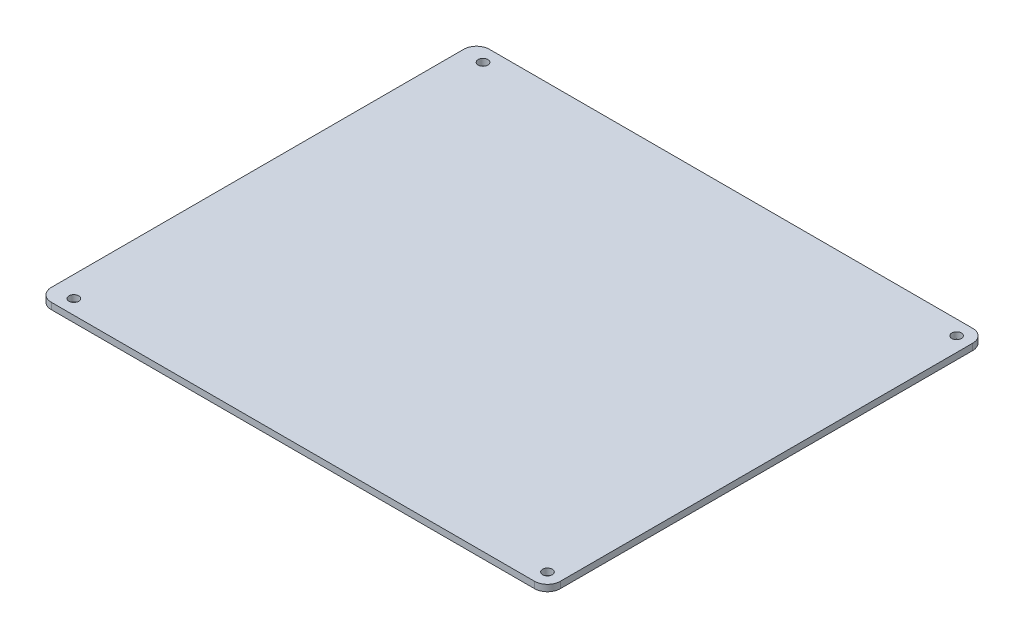
SolidWorks part; units mm, degrees
ref_plane "Front Plane" through (0, 0, 0) normal (0, 0, 1) x (1, 0, 0)
ref_plane "Top Plane" through (0, 0, 0) normal (0, 1, 0) x (1, 0, 0)
ref_plane "Right Plane" through (0, 0, 0) normal (1, 0, 0) x (0, 0, -1)
sketch "Sketch8" plane through (0, 0, 0) normal (0, 1, 0) x (1, 0, 0)
  line L0 (79, 0) -> (65.8191, 0) construction
  line L1 (-79, 68) -> (79, 68)
  line L2 (-79, 68) -> (-79, -68)
  line L3 (-79, -68) -> (79, -68)
  line L4 (79, 68) -> (79, -68)
  circle A0 centre (74.5, 63.5) radius 1.5
  circle A1 centre (-72.5, 63.5) radius 1.5
  circle A2 centre (-72.5, -63.5) radius 1.5
  circle A3 centre (74.5, -63.5) radius 1.5
  point P0 (0, 0)
  dimension "D3" = 3
  dimension "D4" = 4.5
  dimension "D5" = 4.5
  dimension "D6" = 4.5
  dimension "D7" = 6.5
  dimension "D1" = 136
  dimension "D2" = 158
extrude "Boss-Extrude4" add sketch "Sketch8" along normal blind 2
fillet "Fillet2" radius 4 4 edges at (-79, 1, 68) (-79, 1, -68) (79, 1, -68) (79, 1, 68)
sketch "Sketch10" plane through (0, 0, 0) normal (0, -1, 0) x (1, 0, 0)
  line L0 (-79, 0) -> (79, 0) construction
  line L1 (-79, -64) -> (-79, 64) construction
  line L2 (79, 64) -> (79, -64) construction
  line L3 (-65.5, 51) -> (-65.5, -51)
  line L4 (-63.5, 55) -> (63.5, 55)
  line L5 (-67.5, 51) -> (-67.5, -51)
  line L6 (-63.5, -55) -> (63.5, -55)
  line L7 (67.5, 51) -> (67.5, -51)
  line L8 (-67.5, 55) -> (67.5, -55) construction
  line L9 (-67.5, -55) -> (67.5, 55) construction
  line L10 (-63.5, -53) -> (63.5, -53)
  line L11 (65.5, 51) -> (65.5, -51)
  line L12 (-63.5, 53) -> (63.5, 53)
  arc A0 (63.5, 55) -> (67.5, 51) centre (63.5, 51) cw
  arc A1 (63.5, -55) -> (67.5, -51) centre (63.5, -51) ccw
  arc A2 (-67.5, -51) -> (-63.5, -55) centre (-63.5, -51) ccw
  arc A3 (-63.5, 55) -> (-67.5, 51) centre (-63.5, 51) ccw
  arc A4 (-65.5, -51) -> (-63.5, -53) centre (-63.5, -51) ccw
  arc A5 (63.5, -53) -> (65.5, -51) centre (63.5, -51) ccw
  arc A6 (63.5, 53) -> (65.5, 51) centre (63.5, 51) cw
  arc A7 (-63.5, 53) -> (-65.5, 51) centre (-63.5, 51) ccw
  point P6 (0, 0)
  dimension "D3" = 4
  dimension "D1" = 110
  dimension "D2" = 135
  dimension "D4" = 2
extrude "Cut-Extrude1" cut sketch "Sketch10" against normal blind 0.5
sketch "Sketch11" plane through (0, 0, 0) normal (0, -1, 0) x (1, 0, 0)
  line L0 (-65.5, 0) -> (65.5, 0) construction
  line L1 (-65.5, 51) -> (-65.5, -51) construction
  line L2 (65.5, -51) -> (65.5, 51) construction
  line L3 (-63.5, -53) -> (63.5, -53) construction
  line L4 (-55.5, 48) -> (-8.6138, 48)
  line L5 (-59.5, 44) -> (-59.5, -44)
  line L6 (-55.5, -48) -> (-8.6138, -48)
  line L7 (-4.6138, 44) -> (-4.6138, -44)
  line L8 (63.5, 53) -> (-63.5, 53) construction
  line L9 (-57.6, 44) -> (-57.6, -44)
  line L10 (-55.5, -46.1) -> (-8.6138, -46.1)
  line L11 (-6.5138, 44) -> (-6.5138, -44)
  line L12 (-55.5, 46.1) -> (-8.6138, 46.1)
  arc A0 (-59.5, -44) -> (-55.5, -48) centre (-55.5, -44) ccw
  arc A1 (-8.6138, -48) -> (-4.6138, -44) centre (-8.6138, -44) ccw
  arc A2 (-8.6138, 48) -> (-4.6138, 44) centre (-8.6138, 44) cw
  arc A3 (-55.5, 48) -> (-59.5, 44) centre (-55.5, 44) ccw
  arc A4 (-57.6, -44) -> (-55.5, -46.1) centre (-55.5, -44) ccw
  arc A5 (-8.6138, -46.1) -> (-6.5138, -44) centre (-8.6138, -44) ccw
  arc A6 (-8.6138, 46.1) -> (-6.5138, 44) centre (-8.6138, 44) cw
  arc A7 (-55.5, 46.1) -> (-57.6, 44) centre (-55.5, 44) ccw
  point P6 (-35.3166, 0)
  dimension "D1" = 6
  dimension "D2" = 5
  dimension "D3" = 5
  dimension "D4" = 1.9
extrude "Cut-Extrude2" cut sketch "Sketch11" against normal blind 0.5
sketch "Sketch13" plane through (0, 0, 0) normal (0, -1, 0) x (1, 0, 0)
  line L0 (-34.5138, 46) -> (-34.5138, -46) construction
  line L8 (-6.5138, -44) -> (-6.5138, 44) construction
  text T0 "<b>DIKI DARMAWAN</b>\r\n<b>166221064</b>" font "Century Gothic" height in points 24
  dimension "D1" = 28
extrude "Cut-Extrude3" cut sketch "Sketch13" against normal blind 0.5
sketch "Sketch14" plane through (78.7715, 0, -11.0784) normal (0, -1, 0) x (0, 0, 1)
  line L0 (14.3942, 39.3839) -> (14.3942, 38.6607)
  line L1 (14.3942, 38.6607) -> (27.9652, 38.6607)
  line L2 (27.9652, 38.6607) -> (27.9652, 39.1819)
  line L3 (14.3942, 39.3839) -> (24.5365, 39.3839)
  line L4 (24.5365, 39.3839) -> (22.4336, 41.6588)
  line L5 (28.3243, 44.7624) -> (31.9276, 50.2377)
  line L6 (31.9276, 50.2377) -> (32.9334, 50.1306)
  line L7 (33.593, 50.9135) -> (33.0775, 52.0553)
  line L8 (33.0775, 52.0553) -> (37.232, 58.3682)
  line L9 (39.4319, 57.602) -> (43.2952, 51.9087)
  line L10 (43.2952, 51.9087) -> (43.2193, 50.9273)
  line L11 (43.7452, 50.1523) -> (44.5304, 50.002)
  line L12 (44.5304, 50.002) -> (47.4367, 45.7189)
  line L13 (46.1277, 44.114) -> (46.1277, 39.7648)
  line L14 (46.1277, 39.7648) -> (45.8984, 39.7648)
  line L15 (45.8984, 39.7648) -> (45.5136, 39.4091)
  line L16 (45.5136, 39.4091) -> (45.5136, 36.4852)
  line L17 (45.5136, 36.4852) -> (45.8984, 36.0689)
  line L18 (45.8984, 36.0689) -> (46.1277, 36.0689)
  line L19 (46.1277, 36.0689) -> (46.1277, 32.808)
  line L20 (46.1277, 32.808) -> (41.5903, 32.808)
  line L21 (41.5903, 32.808) -> (41.5903, 31.7995)
  line L22 (41.5903, 31.7995) -> (45.8082, 31.7995)
  line L23 (45.8082, 31.7995) -> (45.8082, 30.5822)
  line L24 (45.8082, 30.5822) -> (42.5, 30.5822)
  line L25 (41.7043, 29.6881) -> (41.7043, 24.6699)
  line L26 (41.7043, 24.6699) -> (39.9694, 24.6699)
  line L27 (39.9694, 24.6699) -> (39.9694, 17.6419)
  line L28 (39.9694, 17.6419) -> (58.0715, 17.6419)
  line L29 (58.0715, 17.6419) -> (58.0715, 24.6699)
  line L30 (58.0715, 24.6699) -> (56.627, 24.6699)
  line L31 (56.627, 24.6699) -> (56.627, 29.7373)
  line L32 (55.8459, 30.5822) -> (53.1384, 30.5822)
  line L33 (53.1384, 30.5822) -> (53.1384, 31.7995)
  line L34 (53.1384, 31.7995) -> (56.6276, 31.7995)
  line L35 (56.6276, 31.7995) -> (56.6276, 32.808)
  line L36 (56.6276, 32.808) -> (52.9298, 32.808)
  line L37 (52.9298, 32.808) -> (52.9298, 44.5866)
  line L38 (52.9298, 44.5866) -> (52.7465, 48.0931)
  line L39 (52.7465, 48.0931) -> (44.6522, 60.2848)
  line L40 (44.6522, 60.2848) -> (43.0464, 61.2259)
  line L41 (38.0429, 65.0973) -> (33.3028, 63.2191)
  line L42 (33.3028, 63.2191) -> (23.6089, 48.4889)
  line L43 (23.6089, 48.4889) -> (23.6089, 45.3452)
  line L44 (23.6089, 45.3452) -> (22.5152, 44.114)
  line L45 (25.4242, 46.0787) -> (34.6473, 59.8967)
  line L46 (35.926, 59.0433) -> (26.7841, 45.1709)
  line L47 (40.8051, 58.4574) -> (48.9052, 46.3692)
  line L48 (48.9052, 46.3692) -> (50.0331, 46.3692)
  line L49 (50.0331, 46.3692) -> (41.5903, 58.9689)
  line L50 (43.7452, 59.6351) -> (51.836, 47.4485) construction
  line L59 (45.8082, 30.5822) -> (53.1384, 30.5822)
  line L60 (41.7043, 24.6699) -> (56.627, 24.6699)
  line L61 (43.3305, 22.081) -> (45.974, 22.081)
  line L62 (43.3305, 22.081) -> (43.3305, 18.6903)
  line L63 (43.3305, 18.6903) -> (45.974, 18.6903)
  line L64 (45.974, 22.081) -> (45.974, 18.6903)
  line L65 (43.3305, 22.081) -> (45.974, 18.6903) construction
  line L66 (43.3305, 18.6903) -> (45.974, 22.081) construction
  line L67 (46.1277, 41.9394) -> (52.9298, 41.9394) construction
  line L68 (51.6208, 43.614) -> (51.1208, 44.114)
  line L69 (51.1208, 44.114) -> (47.9367, 44.114)
  line L70 (51.6208, 43.614) -> (51.6208, 40.2648)
  line L71 (51.1208, 39.7648) -> (47.9367, 39.7648)
  line L72 (47.4367, 43.614) -> (47.4367, 40.2648)
  line L73 (51.6208, 44.114) -> (47.4367, 39.7648) construction
  line L74 (51.6208, 39.7648) -> (47.4367, 44.114) construction
  line L75 (47.9367, 44.114) -> (47.4367, 43.614)
  line L76 (47.9367, 39.7648) -> (47.4367, 40.2648)
  line L77 (51.6208, 40.2648) -> (51.1208, 39.7648)
  line L78 (52.9298, 32.808) -> (46.1277, 32.808)
  line L79 (53.1384, 31.7995) -> (45.8082, 31.7995)
  line L80 (51.6208, 32.808) -> (51.6208, 36.3852)
  line L81 (51.5208, 36.4852) -> (50.6923, 36.4852)
  line L82 (50.5923, 36.3852) -> (50.5923, 32.808)
  line L83 (49.5287, 39.7648) -> (49.5287, 38.4099) construction
  line L84 (48.4652, 36.3852) -> (48.4652, 32.808)
  line L85 (47.5367, 36.4852) -> (48.3652, 36.4852)
  line L86 (47.4367, 32.808) -> (47.4367, 36.3852)
  line L87 (48.3652, 36.4852) -> (48.4652, 36.3852)
  line L88 (47.4367, 36.3852) -> (47.5367, 36.4852)
  line L89 (50.6923, 36.4852) -> (50.5923, 36.3852)
  line L90 (51.6208, 36.3852) -> (51.5208, 36.4852)
  arc A0 (27.9652, 39.1819) -> (28.1911, 43.944) centre (26.2751, 41.6485) ccw
  arc A1 (28.3243, 44.7624) -> (28.1911, 43.944) centre (28.6669, 44.2866) ccw
  arc A2 (32.9334, 50.1306) -> (33.593, 50.9135) centre (32.8712, 50.8523) ccw
  arc A3 (37.232, 58.3682) -> (39.4319, 57.602) centre (39.1848, 60.4336) ccw
  arc A4 (43.2193, 50.9273) -> (43.7452, 50.1523) centre (43.8697, 50.8028) ccw
  arc A5 (47.4367, 45.7189) -> (46.1277, 44.114) centre (48.2487, 43.7203) ccw
  arc A6 (42.5, 30.5822) -> (41.7043, 29.6881) centre (42.5492, 29.7373) ccw
  arc A7 (56.627, 29.7373) -> (55.8459, 30.5822) centre (55.814, 29.7692) ccw
  arc A8 (43.0464, 61.2259) -> (41.4746, 62.8115) centre (41.718, 61.4809) ccw
  arc A9 (41.4746, 62.8115) -> (38.0429, 65.0973) centre (38.6158, 62.2385) ccw
  arc A10 (22.5152, 44.114) -> (22.4336, 41.6588) centre (22.08, 42.8995) ccw
  arc A11 (25.4242, 46.0787) -> (26.7841, 45.1709) centre (26.2109, 45.7847) ccw
  arc A12 (34.6473, 59.8967) -> (35.926, 59.0433) centre (35.1931, 59.3298) cw
  arc A13 (40.8051, 58.4574) -> (41.5903, 58.9689) centre (41.1348, 58.8098) cw
  circle A14 centre (25.9948, 41.0458) radius 0.2321
  circle A15 centre (25.9948, 41.0458) radius 0.7503
  circle A16 centre (38.1639, 59.6351) radius 0.3438
  circle A17 centre (38.1639, 59.6351) radius 0.7446
  circle A18 centre (43.7452, 59.6351) radius 0.3297
  circle A19 centre (47.7906, 53.5418) radius 0.2839
  circle A20 centre (51.836, 47.4485) radius 0.2654
  circle A21 centre (47.974, 20.1444) radius 0.6328
  point P92 (44.6522, 20.3856)
  point P95 (49.5287, 41.9394)
  point P113 (51.6208, 36.4852)
  point P115 (50.5923, 36.4852)
  point P118 (48.4652, 36.4852)
  point P120 (47.4367, 36.4852)
  dimension "D1" = 2
extrude "Cut-Extrude5" cut sketch "Sketch14" against normal blind 0.5 contours L60 L26 L27 L28 L29 L30 A21 L61 L64 L63 L62 | L31 A7 L32 L59 L24 A6 L25 L60 | L79 L34 L35 L36 L78 L20 L21 L22 | L44 A10 L4 L3 L0 L1 L2 A0 A1 L5 L6 A2 L7 L8 A3 L9 L10 A4 L11 L12 A5 L13 L14 L15 L16 L17 L18 L19 L78 L86 L88 L85 L87 L84 L82 L89 L81 L90 L80 L37 L38 L39 L40 A8 A9 L41 L42 L43
sketch "Sketch15" plane through (-2.5633, 0, -56.8673) normal (0, -1, 0) x (0, 0, 1)
  line L0 (10.2975, -55.1047) -> (10.2975, -59.7552)
  line L1 (13.2978, -59.7552) -> (13.2978, -55.1047)
  line L2 (13.2978, -55.1047) -> (16.2026, -55.1047)
  line L3 (16.2026, -55.1047) -> (16.2026, -62.6486)
  line L4 (19.2148, -62.6486) -> (19.2148, -55.1047)
  line L5 (19.2148, -55.1047) -> (20.6726, -55.1047)
  line L6 (20.6726, -55.1047) -> (20.6726, -56.8684)
  line L7 (23.6407, -56.8684) -> (23.6407, -53.4424)
  line L8 (26.5927, -53.4424) -> (26.5927, -56.8684)
  line L9 (29.5754, -56.8684) -> (29.5754, -53.4424)
  line L10 (32.5183, -53.4424) -> (32.5183, -59.7552)
  line L11 (35.4991, -59.7552) -> (35.4991, -53.4424)
  line L12 (38.4074, -53.4424) -> (38.4074, -56.8684)
  line L13 (41.4124, -53.4424) -> (41.4124, -56.8684)
  line L14 (44.3284, -53.4424) -> (44.3284, -59.7552)
  line L15 (47.3334, -53.4424) -> (47.3334, -59.7552)
  line L16 (50.2716, -59.7552) -> (50.2716, -53.4424)
  line L17 (53.2543, -53.4424) -> (53.2543, -59.7552)
  line L18 (56.1944, -53.4424) -> (56.1944, -59.7552)
  line L19 (59.1516, -56.324) -> (59.1516, -53.4424)
  line L20 (65.0441, -55.1047) -> (65.0441, -53.4424)
  line L21 (73.9671, -53.4424) -> (73.9671, -59.7552)
  line L22 (65.0441, -58.0472) -> (65.0441, -59.7552)
  line L23 (62.0939, -58.0472) -> (62.0939, -59.7552)
  line L24 (62.0939, -58.0472) -> (65.0441, -58.0472)
  line L25 (65.0441, -55.1047) -> (60.3333, -55.1047)
  line L26 (10.2975, -55.1047) -> (8.562, -55.1047)
  line L27 (8.562, -52.1704) -> (10.2975, -52.1704)
  line L28 (10.2975, -52.1704) -> (10.2975, -48.7913)
  line L29 (13.2978, -52.1704) -> (13.2978, -48.7913)
  line L30 (13.2978, -52.1704) -> (20.6726, -52.1704)
  line L31 (20.6726, -52.1704) -> (20.9271, -52.1704)
  line L32 (16.2026, -48.8276) -> (16.2026, -49.5068)
  arc A0 (10.2975, -59.7552) -> (13.2978, -59.7552) centre (11.7977, -59.5968) ccw
  arc A1 (16.2026, -62.6486) -> (19.2148, -62.6486) centre (17.7087, -62.4906) ccw
  arc A2 (20.6726, -56.8684) -> (23.6407, -56.8684) centre (22.1567, -56.5753) ccw
  arc A3 (23.6407, -53.4424) -> (26.5927, -53.4424) centre (25.1167, -53.6627) cw
  arc A4 (26.5927, -56.8684) -> (29.5754, -56.8684) centre (28.084, -56.5703) ccw
  arc A5 (53.2543, -53.4424) -> (56.1944, -53.4424) centre (54.7243, -53.6809) cw
  arc A6 (59.1516, -53.4424) -> (50.2716, -53.4424) centre (54.7116, -53.6051) ccw
  arc A7 (68.0198, -53.4424) -> (71.0256, -53.4424) centre (69.5227, -53.6514) cw
  arc A8 (71.0256, -53.4424) -> (79.9574, -53.4424) centre (75.4915, -53.6688) cw
  arc A9 (73.9671, -53.4424) -> (76.9086, -53.4424) centre (75.4378, -53.6389) cw
  arc A10 (76.9086, -53.4424) -> (79.9574, -53.4424) centre (78.433, -53.5787) ccw
  arc A11 (65.0441, -59.7552) -> (68.0198, -59.7552) centre (66.5319, -59.5876) ccw
  arc A12 (68.0198, -59.7552) -> (71.0256, -59.7552) centre (69.5227, -59.549) ccw
  arc A13 (71.0256, -59.7552) -> (73.9671, -59.7552) centre (72.4964, -59.6081) ccw
  arc A14 (62.161, -53.4424) -> (59.2376, -53.4424) centre (60.6993, -53.5823) cw
  arc A15 (62.0939, -59.7552) -> (59.1516, -59.7968) centre (60.6205, -59.6157) cw
  arc A16 (59.1516, -59.7968) -> (56.1944, -59.7552) centre (57.6762, -59.5455) cw
  arc A17 (50.2716, -59.7552) -> (47.5363, -60.3551) centre (48.7925, -59.5472) cw
  arc A18 (47.5363, -60.3551) -> (44.5897, -61.0014) centre (45.7398, -59.2049) cw
  arc A19 (44.5897, -61.0014) -> (53.2543, -59.7552) centre (48.8075, -59.5823) ccw
  arc A20 (44.3284, -59.7552) -> (47.3334, -59.7552) centre (45.8309, -59.5186) ccw
  arc A21 (38.4074, -56.8684) -> (41.4124, -56.8684) centre (39.9099, -56.5582) ccw
  arc A22 (32.5183, -59.7552) -> (35.4991, -59.7552) centre (34.0087, -59.5731) ccw
  arc A23 (29.5754, -53.4424) -> (32.5183, -53.4424) centre (31.0469, -53.6421) cw
  arc A24 (35.4991, -53.4424) -> (38.4074, -53.4424) centre (36.9533, -53.6486) cw
  arc A25 (41.4124, -53.4424) -> (44.3284, -53.4424) centre (42.8704, -53.6094) cw
  arc A26 (8.562, -55.1047) -> (8.562, -52.1704) centre (8.8059, -53.6375) cw
  arc A27 (20.9271, -52.1704) -> (28.084, -50.3247) centre (25.1108, -53.5942) cw
  arc A28 (28.084, -50.3247) -> (34.0087, -50.3247) centre (31.0464, -53.742) cw
  arc A29 (34.0087, -50.3247) -> (39.9099, -50.3247) centre (36.9593, -53.6418) cw
  arc A30 (39.9099, -50.3247) -> (47.3334, -53.4424) centre (42.9035, -53.5935) cw
  arc A31 (10.2975, -48.7913) -> (19.2148, -49.5068) centre (14.746, -49.2753) cw
  arc A32 (13.2978, -48.7913) -> (16.2026, -48.8276) centre (14.7451, -49.2206) cw
  arc A33 (19.2148, -49.5068) -> (16.2026, -49.5068) centre (17.7087, -49.1887) cw
  arc A34 (65.0441, -53.4424) -> (62.161, -53.4424) centre (63.6025, -53.5981) ccw
  arc A35 (59.2376, -53.4424) -> (68.0198, -53.4424) centre (63.6287, -53.5935) cw
  arc A36 (59.1516, -56.324) -> (60.3333, -55.1047) centre (60.8174, -56.7561) cw
  circle A37 centre (69.5227, -50.5608) radius 1.2093
extrude "Cut-Extrude6" cut sketch "Sketch15" against normal blind 0.5
